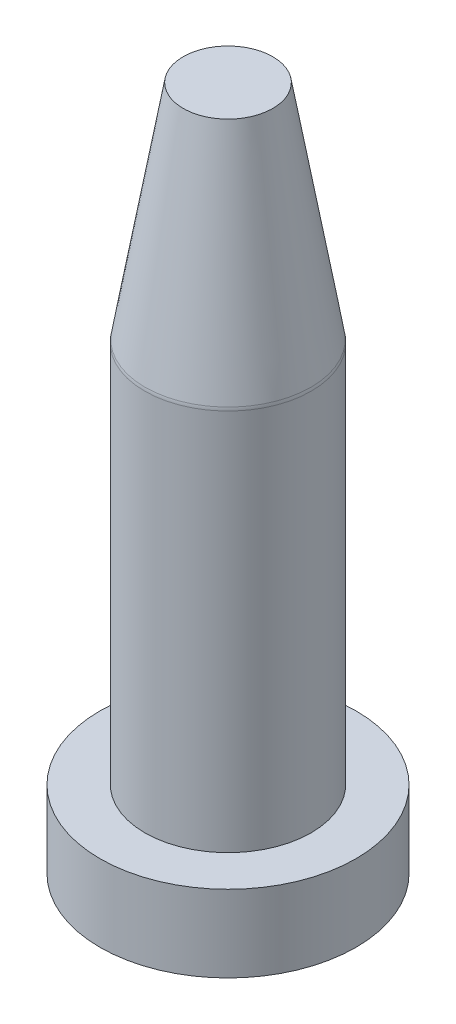
SolidWorks part; units mm, degrees
ref_plane "前视" through (0, 0, 0) normal (0, 0, 1) x (1, 0, 0)
ref_plane "上视" through (0, 0, 0) normal (0, 1, 0) x (1, 0, 0)
ref_plane "右视" through (0, 0, 0) normal (1, 0, 0) x (0, 0, -1)
sketch "草图1" plane through (0, 0, 0) normal (0, 0, 1) x (1, 0, 0)
  line L0 (0, 0) -> (0, 101.922) construction
  line L1 (0, 0) -> (20, 0)
  line L2 (20, 0) -> (20, 12)
  line L3 (20, 12) -> (13, 12)
  line L4 (13, 12) -> (13, 72)
  line L5 (0, 107) -> (7, 107)
  line L6 (7, 107) -> (13, 72)
  line L7 (0, 0) -> (0, 107)
  point P7 (0, 107)
  dimension "D1" = 20
  dimension "D2" = 12
  dimension "D3" = 7
  dimension "D4" = 60
  dimension "D5" = 107
  dimension "D6" = 7
revolve "基体-旋转" add sketch "草图1" angle 360 about L0
fillet "圆角1" radius 3 1 edges at (0, 72, -13)
